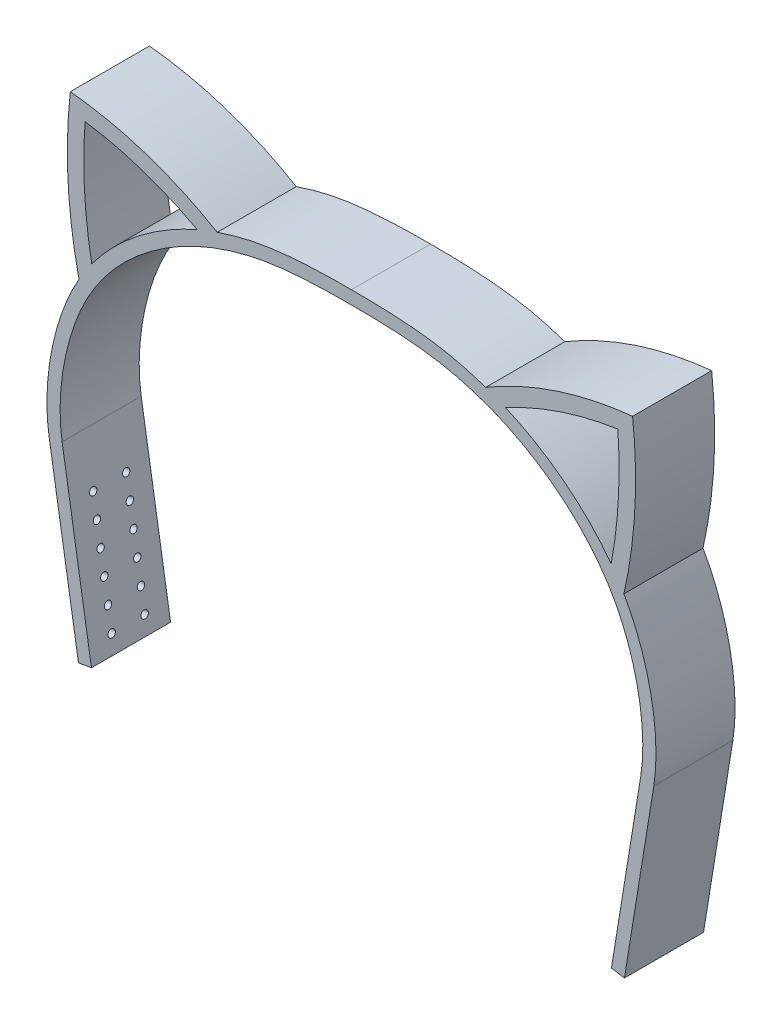
SolidWorks part; units mm, degrees
ref_plane "前视基准面" through (0, 0, 0) normal (0, 0, 1) x (1, 0, 0)
ref_plane "上视基准面" through (0, 0, 0) normal (0, 1, 0) x (1, 0, 0)
ref_plane "右视基准面" through (0, 0, 0) normal (1, 0, 0) x (0, 0, -1)
other "Configuration Table"
sketch "草图1" plane through (0, 0, 0) normal (0, 0, 1) x (1, 0, 0)
  line L0 (-90, -2.8215) -> (-75.7241, -90.8242) construction
  line L1 (0, -1.5998) -> (0, 96.5061) construction
  line L2 (-91.7465, 11.9822) -> (-82.8362, -42.9449)
  line L6 (-90, -2.8215) -> (-75.7241, -90.8242) construction
  line L12 (-69.6822, 237.1471) -> (218.3178, 237.1471) construction
  line L13 (-87.7981, 12.6227) -> (-78.8878, -42.3044)
  line L14 (-82.8362, -42.9449) -> (-78.8878, -42.3044)
  line L15 (0, 96.5061) -> (0, 92.5061)
  line L18 (-91.6098, 1.7593) -> (-90.4204, 1.9342)
  line L20 (-91.6098, 1.7593) -> (-90.4204, 1.9342)
  parabola Q0 (-85.8689, 2.6033) -> (-83.692, 2.9233) focus (19598.7033, -133910.4101) apex (-86.4187, 2.5224)
  parabola Q1 (-85.8689, 2.6033) -> (-83.692, 2.9233) focus (19598.7033, -133910.4101) apex (-86.4187, 2.5224) construction
  spline S0 degree 3 poles (-91.7465, 11.9822) (-93.9274, 25.4262) (-88.4066, 57.1286) (-60.7485, 83.1863) (-36.3999, 93.6337) (-19.0224, 96.1703) (-5.9746, 96.5061) (0, 96.5061) knots 0 0 0 0 0.265223 0.454794 0.639115 0.853786 1 1 1 1
  spline S1 degree 1 poles (-87.7981, 12.6227) (0, 92.5061) knots 0 0 1 1 construction
  spline S2 degree 3 poles (-87.7981, 12.6227) (-87.918, 13.3615) (-88.1156, 14.8223) (-88.3864, 17.9484) (-88.466, 22.0697) (-88.1489, 27.2893) (-87.1759, 34.457) (-84.9368, 43.552) (-80.701, 53.8725) (-74.9817, 62.7793) (-68.0674, 70.3771) (-60.5318, 76.6338) (-52.9779, 81.5051) (-45.6714, 85.1463) (-38.6839, 87.8019) (-32.2065, 89.6832) (-26.1336, 90.9376) (-20.1344, 91.725) (-14.9565, 92.1178) (-10.6194, 92.3277) (-7.2472, 92.4337) (-4.3106, 92.4837) (-1.8831, 92.503) (-0.6239, 92.5061) (0, 92.5061) knots 0 0 0 0 0.015625 0.03125 0.0625 0.09375 0.125 0.1875 0.25 0.3125 0.375 0.4375 0.5 0.5625 0.625 0.6875 0.75 0.8125 0.875 0.90625 0.9375 0.96875 0.984375 1 1 1 1
  spline S4 degree 2 poles (-85.3038, 105.8984) (-61.3825, 103.4319) (-40.7496, 91.2236) knots 0 0 0 1 1 1
  spline S5 degree 2 poles (-85.3038, 105.8984) (-88.0091, 81.6833) (-82.6724, 57.9266) knots 0 0 0 1 1 1
  spline S6 degree 1 poles (-80.809, 100.2912) (-77.7939, 59.0225) knots 0 0 1 1 construction
  spline S7 degree 1 poles (-80.809, 100.2912) (-43.2958, 86.9204) knots 0 0 1 1 construction
  spline S8 degree 2 poles (-77.7939, 59.0225) (-78.2023, 60.8403) (-78.8018, 63.8754) (-81.1109, 76.7404) (-81.2583, 94.3778) (-80.809, 100.2912) knots 0.108068 0.108068 0.108068 0.18727 0.240071 0.74669 1 1 1 only from (-78.7964, 63.8755) to (-80.809, 100.2912)
  spline S9 degree 2 poles (-80.809, 100.2912) (-74.9542, 99.4111) (-58.067, 94.8919) (-46.7683, 88.895) (-44.5887, 87.6854) (-43.2958, 86.9204) knots 0.110322 0.110322 0.110322 0.370438 0.890671 0.934403 1 1 1 only from (-80.809, 100.2912) to (-46.7694, 88.8903)
  point P32 (-85.2378, -38.506)
  dimension "D2" = 5
  dimension "D1" = 4
  dimension "D3" = 6.5
extrude "凸台-拉伸1" add sketch "草图1" along normal blind 24
sketch "草图2" plane through (-83.5517, -13.5539, 0) normal (0.9871, 0.1601, 0) x (0, 0, -1)
  line L0 (-17.0277, 11.0954) -> (-7.0308, 11.0954) construction
  line L1 (-17.0277, 4.0954) -> (-7.0308, 4.0954) construction
  line L2 (-17.0277, -2.9046) -> (-7.0308, -2.9046) construction
  line L3 (-17.0277, -9.9046) -> (-7.0308, -9.9046) construction
  line L4 (-17.0277, -16.9046) -> (-7.0308, -16.9046) construction
  line L5 (-17.0277, -23.9046) -> (-7.0308, -23.9046) construction
  ellipse E0 centre (-7.0308, 11.0954) end of major axis (-7.2161, 12.281) minor radius 1.1996 construction
  ellipse E1 centre (-17.0277, 11.0954) end of major axis (-17.2131, 12.281) minor radius 1.1996 construction
  ellipse E2 centre (-7.0308, 11.0954) end of major axis (-7.2161, 12.281) minor radius 1.1996 construction
  ellipse E3 centre (-17.0277, 11.0954) end of major axis (-17.2131, 12.281) minor radius 1.1996 construction
  point P24 (-7.0308, 11.0954)
  point P25 (-17.0277, 11.0954)
  point P35 (-17.0277, 4.0954)
  point P36 (-17.0277, -2.9046)
  point P37 (-17.0277, -9.9046)
  point P38 (-17.0277, -16.9046)
  point P39 (-17.0277, -23.9046)
  point P40 (-7.0308, -23.9046)
  point P41 (-7.0308, -16.9046)
  point P42 (-7.0308, -9.9046)
  point P43 (-7.0308, -2.9046)
  point P44 (-7.0308, 4.0954)
  dimension "D1" = 6
hole_wizard "Ø2.0mm 暗销孔1" positions "草图2" profile "草图3" hole size "Ø2.0" standard "GB"
sketch "草图3" plane through (-84.2075, -9.5114, 7.0308) normal (0, 0, 1) x (-0.1601, 0.9871, 0)
  line L0 (0, 0) -> (0, 2.6609)
  line L1 (0, 2.6609) -> (1.1, 2)
  line L2 (1.1, 2) -> (1.1, 0)
  line L5 (1.1, 0) -> (0, 0)
  line L10 (0, 2.6609) -> (-1.1, 2) construction
  line L11 (0, -6.35) -> (0, 107.95) construction
  dimension "孔直径" = 2.2
  dimension "孔深度" = 2
  dimension "导头角度" = 118
mirror "镜向1" about plane through (0, 0, 24) normal (1, 0, 0) of bodies 108 106
ref_plane "基准面1" through (-90, 0, 0) normal (1, 0, 0) x (0, 0, -1)
